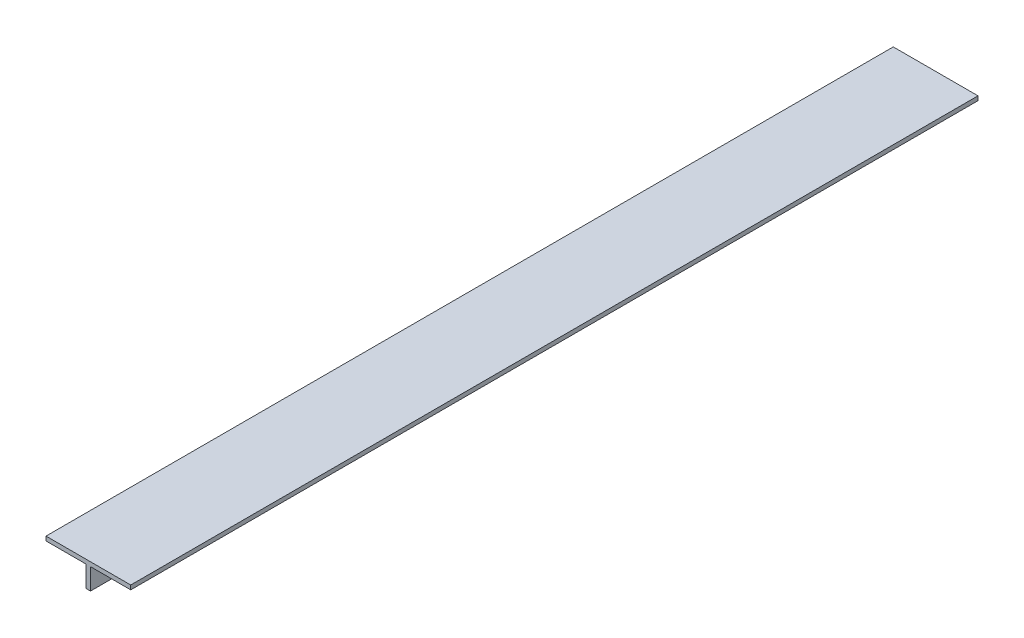
SolidWorks part; units mm, degrees
ref_plane "Front Plane" through (0, 0, 0) normal (0, 0, 1) x (1, 0, 0)
ref_plane "Top Plane" through (0, 0, 0) normal (0, 1, 0) x (1, 0, 0)
ref_plane "Right Plane" through (0, 0, 0) normal (1, 0, 0) x (0, 0, -1)
other "Configuration Table"
sketch "Sketch1" plane through (0, 0, 0) normal (0, 0, 1) x (1, 0, 0)
  line L0 (0, 0) -> (5080, 0)
  line L1 (0, 0) -> (0, -254)
  line L2 (0, -254) -> (2413, -254)
  line L3 (2413, -254) -> (2413, -1524)
  line L4 (2413, -1524) -> (2667, -1524)
  line L5 (2667, -1524) -> (2667, -254)
  line L6 (2667, -254) -> (5080, -254)
  line L7 (5080, -254) -> (5080, 0)
extrude "Extrude1" add sketch "Sketch1" along normal blind 50800
